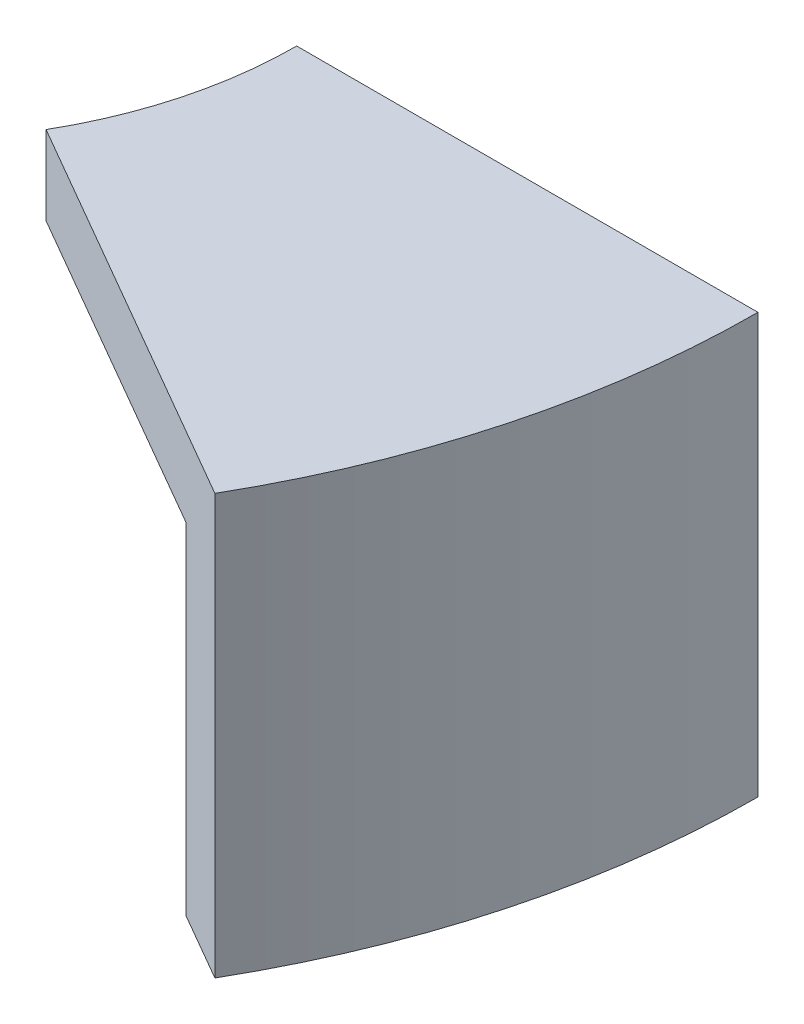
SolidWorks part; units mm, degrees
ref_plane "Front Plane" through (0, 0, 0) normal (0, 0, 1) x (1, 0, 0)
ref_plane "Top Plane" through (0, 0, 0) normal (0, 1, 0) x (1, 0, 0)
ref_plane "Right Plane" through (0, 0, 0) normal (1, 0, 0) x (0, 0, -1)
sketch "Sketch1" plane through (0, 0, 0) normal (0, 0, 1) x (1, 0, 0)
  line L0 (197.8699, 906.5599) -> (337.8699, 906.5599) construction
  line L1 (297.8699, 906.5599) -> (332.8699, 906.5599)
  line L2 (297.8699, 906.5599) -> (297.8699, 900.5599)
  line L3 (297.8699, 900.5599) -> (326.8699, 900.5599)
  line L4 (332.8699, 906.5599) -> (332.8699, 902.5599)
  line L5 (267.8699, 911.5599) -> (267.8699, 853.6092) construction
  line L7 (326.8699, 900.5599) -> (326.8699, 874.7094)
  line L8 (326.8699, 874.7094) -> (332.8699, 874.7094)
  line L9 (332.8699, 902.5599) -> (332.8699, 874.7094)
  dimension "D1" = 6
  dimension "D2" = 6
  dimension "D3" = 29
  dimension "D4" = 30
revolve "Revolve1" add sketch "Sketch1" angle 30 about L5
